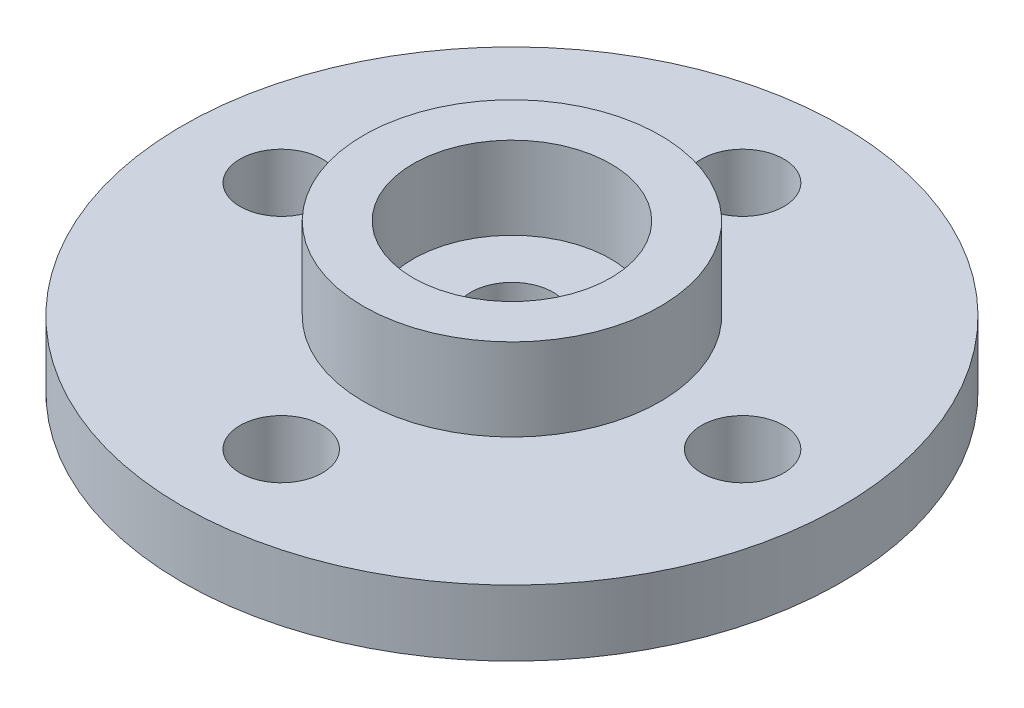
SolidWorks part; units mm, degrees
ref_plane "Спереди" through (0, 0, 0) normal (0, 0, 1) x (1, 0, 0)
ref_plane "Сверху" through (0, 0, 0) normal (0, 1, 0) x (1, 0, 0)
ref_plane "Справа" through (0, 0, 0) normal (1, 0, 0) x (0, 0, -1)
sketch "Эскиз1" plane through (0, 0, 0) normal (0, 1, 0) x (1, 0, 0)
  line L0 (0, 0) -> (7, 0) construction
  line L1 (0, 0) -> (0, -7) construction
  line L2 (0, 0) -> (-7, 0) construction
  line L3 (0, 0) -> (0, 7) construction
  circle A0 centre (0, 0) radius 10
  circle A1 centre (7, 0) radius 1.25
  circle A2 centre (0, 0) radius 1.25
  circle A3 centre (0, -7) radius 1.25
  circle A4 centre (-7, 0) radius 1.25
  circle A5 centre (0, 7) radius 1.25
  point P15 (0, 0)
  dimension "D1" = 4
extrude "Бобышка-Вытянуть1" add sketch "Эскиз1" along normal blind 2
sketch "Эскиз2" plane through (0, 2, 0) normal (0, 1, 0) x (1, 0, 0)
  circle A0 centre (0, 0) radius 3
  circle A1 centre (0, 0) radius 4.5
extrude "Бобышка-Вытянуть2" add sketch "Эскиз2" along normal blind 2.5
